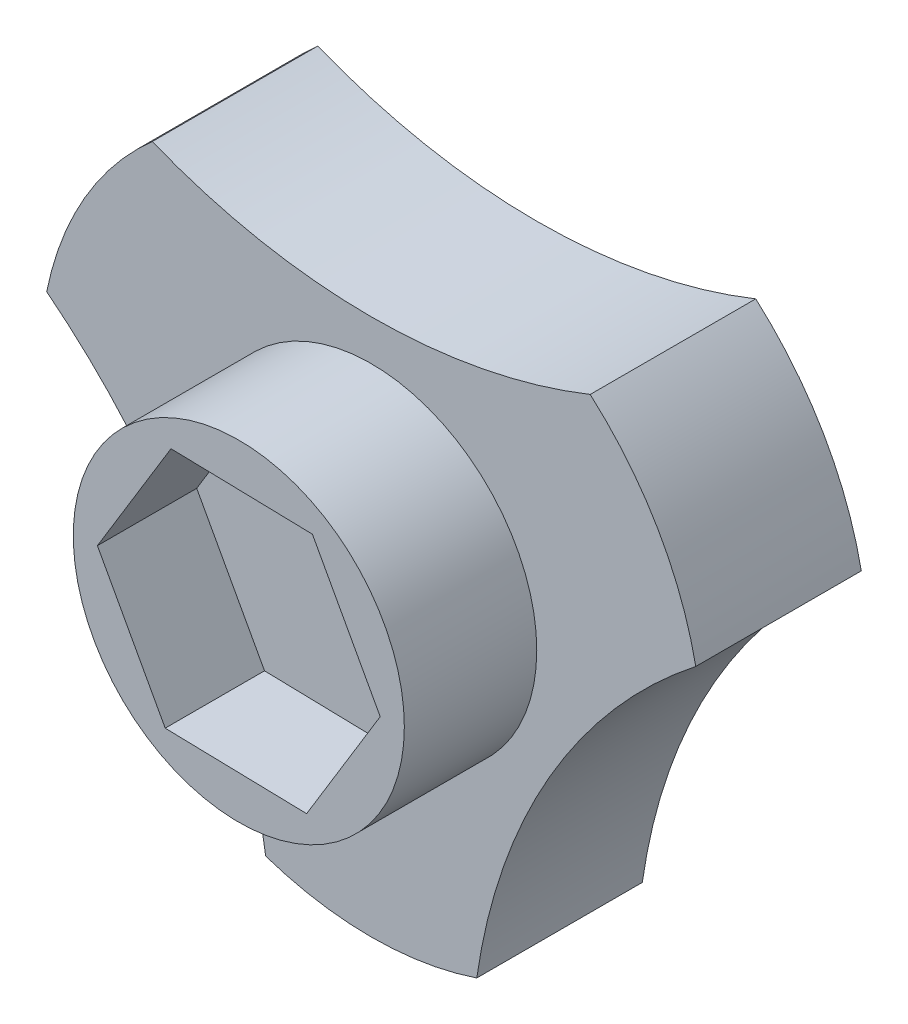
SolidWorks part; units mm, degrees
ref_plane "Front Plane" through (0, 0, 0) normal (0, 0, 1) x (1, 0, 0)
ref_plane "Top Plane" through (0, 0, 0) normal (0, 1, 0) x (1, 0, 0)
ref_plane "Right Plane" through (0, 0, 0) normal (1, 0, 0) x (0, 0, -1)
sketch "Sketch1" plane through (0, 0, 0) normal (0, 0, 1) x (1, 0, 0)
  circle A0 centre (0, 0) radius 10
  dimension "D1" = 20
extrude "Boss-Extrude1" add sketch "Sketch1" along normal blind 5
sketch "Sketch2" plane through (0, 0, 5) normal (0, 0, 1) x (1, 0, 0)
  circle A0 centre (0, 0) radius 5
  dimension "D1" = 10
extrude "Boss-Extrude2" add sketch "Sketch2" along normal blind 4
sketch "Sketch3" plane through (0, 0, 9) normal (0, 0, 1) x (1, 0, 0)
  line L1 (2.0482, -3.7494) -> (4.2712, -0.1009)
  line L2 (4.2712, -0.1009) -> (2.223, 3.6485)
  line L3 (2.223, 3.6485) -> (-2.0482, 3.7494)
  line L4 (-2.0482, 3.7494) -> (-4.2712, 0.1009)
  line L5 (-4.2712, 0.1009) -> (-2.223, -3.6485)
  line L6 (-2.223, -3.6485) -> (2.0482, -3.7494)
  circle A0 centre (0, 0) radius 3.7 construction
  dimension "D1" = 7.4
extrude "Cut-Extrude1" cut sketch "Sketch3" against normal blind 3
sketch "Sketch4" plane through (0, 0, 5) normal (0, 0, 1) x (1, 0, 0)
  line L0 (0, 0) -> (0, 10) construction
  line L1 (0, 10) -> (0, 7.5) construction
  line L2 (0, 7.5) -> (-8.2368, 7.5) construction
  line L3 (-8.2368, 7.5) -> (10.5901, 7.5) construction
  circle A0 centre (0, 0) radius 10 construction
  arc A1 (-6.6144, 7.5) -> (6.6144, 7.5) centre (0, 24) ccw
  arc A2 (9.8024, 1.9782) -> (3.188, -9.4782) centre (20.7846, -12) ccw
  arc A3 (-3.188, -9.4782) -> (-9.8024, 1.9782) centre (-20.7846, -12) ccw
  point P20 (0, 0)
  dimension "D2" = 14
  dimension "D1" = 2.5
  dimension "D3" = 3
extrude "Cut-Extrude-Thin1" cut sketch "Sketch4" against normal blind 5 thin thin type one direction reverse wall 10
